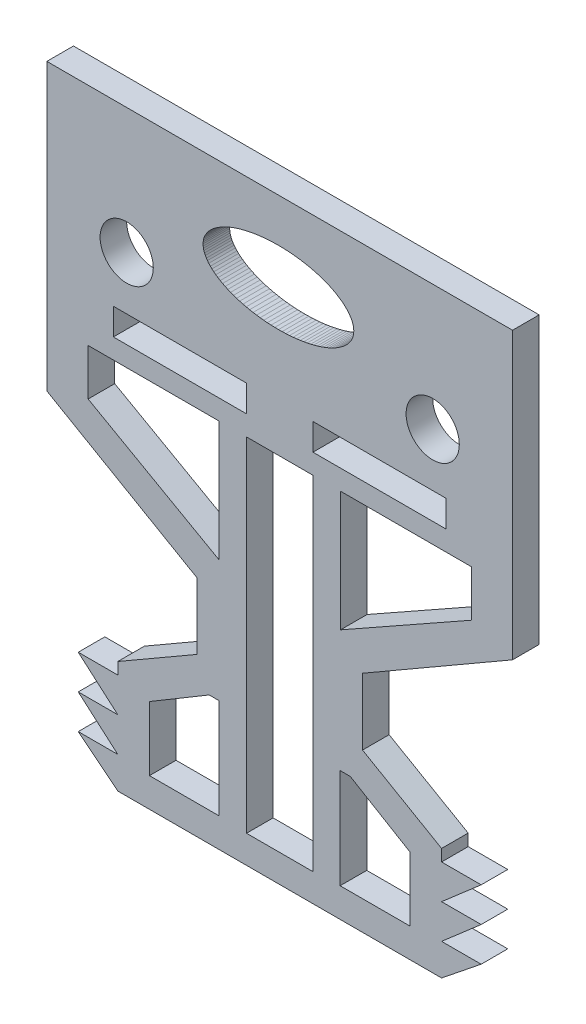
SolidWorks part; units mm, degrees
ref_plane "前视基准面" through (0, 0, 0) normal (0, 0, 1) x (1, 0, 0)
ref_plane "上视基准面" through (0, 0, 0) normal (0, 1, 0) x (1, 0, 0)
ref_plane "右视基准面" through (0, 0, 0) normal (1, 0, 0) x (0, 0, -1)
sketch "Model" plane through (0, 0, 0) normal (0, 0, 1) x (1, 0, 0)
  line L0 (794.8264, 604.0866) -> (759.8264, 604.0866)
  line L1 (789.8264, 590.6477) -> (789.8264, 588.6477)
  line L2 (789.8264, 590.6477) -> (779.8264, 590.6477)
  line L3 (779.8264, 588.6477) -> (779.8264, 590.6477)
  line L4 (774.8264, 590.6477) -> (764.8264, 590.6477)
  line L5 (764.8264, 588.6477) -> (764.8264, 590.6477)
  line L6 (789.8264, 588.6477) -> (779.8264, 588.6477)
  line L7 (774.8264, 588.6477) -> (764.8264, 588.6477)
  line L8 (774.8264, 590.6477) -> (774.8264, 588.6477)
  line L9 (789.4934, 559.2567) -> (765.1593, 559.2567)
  line L10 (783.5518, 576.1218) -> (783.5518, 571.1218)
  line L11 (783.5518, 571.1218) -> (789.4934, 567.6914)
  line L12 (794.8264, 604.0866) -> (794.8264, 582.6312)
  line L13 (759.8264, 604.0866) -> (759.8264, 582.6312)
  line L14 (783.5518, 576.1218) -> (794.8264, 582.6312)
  line L15 (771.101, 576.1218) -> (771.101, 571.1218)
  line L16 (771.101, 571.1218) -> (765.1593, 567.6914)
  line L17 (771.101, 576.1218) -> (759.8264, 582.6312)
  line L18 (792.4681, 566.808) -> (789.4934, 566.808)
  line L19 (792.4681, 564.2247) -> (789.4934, 564.2247)
  line L20 (789.4934, 564.2247) -> (792.4681, 566.808)
  line L21 (792.4681, 561.6414) -> (789.4934, 561.6414)
  line L22 (789.4934, 561.6414) -> (792.4681, 564.2247)
  line L23 (792.4681, 561.6414) -> (789.4934, 559.2567)
  line L24 (789.4934, 566.808) -> (789.4934, 567.6914)
  line L25 (762.1846, 566.808) -> (765.1593, 566.808)
  line L26 (762.1846, 564.2247) -> (765.1593, 564.2247)
  line L27 (765.1593, 564.2247) -> (762.1846, 566.808)
  line L28 (762.1846, 561.6414) -> (765.1593, 561.6414)
  line L29 (765.1593, 561.6414) -> (762.1846, 564.2247)
  line L30 (762.1846, 561.6414) -> (765.1593, 559.2567)
  line L31 (765.1593, 566.808) -> (765.1593, 567.6914)
  line L32 (791.725, 587.1462) -> (781.8947, 587.1462)
  line L33 (781.8947, 587.1462) -> (781.8947, 578.1181)
  line L34 (781.8947, 578.1181) -> (791.725, 583.6595)
  line L35 (791.725, 583.6595) -> (791.725, 587.1462)
  line L36 (779.8203, 587.1462) -> (779.8203, 561.3469)
  line L37 (787.1169, 566.2716) -> (782.6295, 568.9454)
  line L38 (782.6295, 568.9454) -> (781.8695, 568.9454)
  line L39 (781.8695, 568.9454) -> (781.8695, 561.4489)
  line L40 (781.8695, 561.4489) -> (787.1169, 561.4489)
  line L41 (787.1169, 561.4489) -> (787.1169, 566.2716)
  line L42 (762.9277, 587.1462) -> (772.758, 587.1462)
  line L43 (772.758, 587.1462) -> (772.758, 578.1181)
  line L44 (772.758, 578.1181) -> (762.9277, 583.6595)
  line L45 (762.9277, 583.6595) -> (762.9277, 587.1462)
  line L46 (774.8324, 587.1462) -> (774.8324, 561.3469)
  line L47 (774.8324, 587.1462) -> (779.8203, 587.1462)
  line L48 (779.8203, 561.3469) -> (774.8324, 561.3469)
  line L49 (767.5358, 566.2716) -> (772.0232, 568.9454)
  line L50 (772.7832, 568.9454) -> (772.7832, 561.4489)
  line L51 (772.7832, 561.4489) -> (767.5358, 561.4489)
  line L52 (767.5358, 561.4489) -> (767.5358, 566.2716)
  line L53 (772.7832, 568.9454) -> (772.0232, 568.9454)
  line L54 (782.8963, 598.0742) -> (782.8863, 598.2082)
  line L55 (782.8863, 598.2082) -> (782.8663, 598.3432)
  line L56 (782.8663, 598.3432) -> (782.8363, 598.4762)
  line L57 (782.8363, 598.4762) -> (782.7863, 598.6082)
  line L58 (782.7863, 598.6082) -> (782.7263, 598.7402)
  line L59 (782.7263, 598.7402) -> (782.6463, 598.8692)
  line L60 (782.6463, 598.8692) -> (782.5663, 598.9972)
  line L61 (782.5663, 598.9972) -> (782.4663, 599.1222)
  line L62 (782.4663, 599.1222) -> (782.3463, 599.2452)
  line L63 (782.3463, 599.2452) -> (782.2263, 599.3652)
  line L64 (782.2263, 599.3652) -> (782.0863, 599.4832)
  line L65 (782.0863, 599.4832) -> (781.9363, 599.5962)
  line L66 (781.9363, 599.5962) -> (781.7763, 599.7062)
  line L67 (781.7763, 599.7062) -> (781.6063, 599.8122)
  line L68 (781.6063, 599.8122) -> (781.4263, 599.9142)
  line L69 (781.4263, 599.9142) -> (781.2363, 600.0112)
  line L70 (781.2363, 600.0112) -> (781.0363, 600.1042)
  line L71 (781.0363, 600.1042) -> (780.8263, 600.1922)
  line L72 (780.8263, 600.1922) -> (780.6063, 600.2752)
  line L73 (780.6063, 600.2752) -> (780.3763, 600.3522)
  line L74 (780.3763, 600.3522) -> (780.1463, 600.4242)
  line L75 (780.1463, 600.4242) -> (779.8963, 600.4902)
  line L76 (779.8963, 600.4902) -> (779.6563, 600.5512)
  line L77 (779.6563, 600.5512) -> (779.3963, 600.6052)
  line L78 (779.3963, 600.6052) -> (779.1363, 600.6542)
  line L79 (779.1363, 600.6542) -> (778.8763, 600.6962)
  line L80 (778.8763, 600.6962) -> (778.6063, 600.7322)
  line L81 (778.6063, 600.7322) -> (778.3363, 600.7612)
  line L82 (778.3363, 600.7612) -> (778.0663, 600.7842)
  line L83 (778.0663, 600.7842) -> (777.7863, 600.8012)
  line L84 (777.7863, 600.8012) -> (777.5063, 600.8102)
  line L85 (777.5063, 600.8102) -> (777.2363, 600.8142)
  line L86 (777.2363, 600.8142) -> (776.9563, 600.8102)
  line L87 (776.9563, 600.8102) -> (776.6763, 600.8012)
  line L88 (776.6763, 600.8012) -> (776.3963, 600.7842)
  line L89 (776.3963, 600.7842) -> (776.1263, 600.7612)
  line L90 (776.1263, 600.7612) -> (775.8563, 600.7322)
  line L91 (775.8563, 600.7322) -> (775.5863, 600.6962)
  line L92 (775.5863, 600.6962) -> (775.3263, 600.6542)
  line L93 (775.3263, 600.6542) -> (775.0663, 600.6052)
  line L94 (775.0663, 600.6052) -> (774.8063, 600.5512)
  line L95 (774.8063, 600.5512) -> (774.5663, 600.4902)
  line L96 (774.5663, 600.4902) -> (774.3163, 600.4242)
  line L97 (774.3163, 600.4242) -> (774.0863, 600.3522)
  line L98 (774.0863, 600.3522) -> (773.8563, 600.2752)
  line L99 (773.8563, 600.2752) -> (773.6363, 600.1922)
  line L100 (773.6363, 600.1922) -> (773.4263, 600.1042)
  line L101 (773.4263, 600.1042) -> (773.2263, 600.0112)
  line L102 (773.2263, 600.0112) -> (773.0363, 599.9142)
  line L103 (773.0363, 599.9142) -> (772.8563, 599.8122)
  line L104 (772.8563, 599.8122) -> (772.6863, 599.7062)
  line L105 (772.6863, 599.7062) -> (772.5263, 599.5962)
  line L106 (772.5263, 599.5962) -> (772.3763, 599.4832)
  line L107 (772.3763, 599.4832) -> (772.2363, 599.3652)
  line L108 (772.2363, 599.3652) -> (772.1163, 599.2452)
  line L109 (772.1163, 599.2452) -> (771.9963, 599.1222)
  line L110 (771.9963, 599.1222) -> (771.8963, 598.9972)
  line L111 (771.8963, 598.9972) -> (771.8163, 598.8692)
  line L112 (771.8163, 598.8692) -> (771.7363, 598.7402)
  line L113 (771.7363, 598.7402) -> (771.6763, 598.6082)
  line L114 (771.6763, 598.6082) -> (771.6263, 598.4762)
  line L115 (771.6263, 598.4762) -> (771.5963, 598.3432)
  line L116 (771.5963, 598.3432) -> (771.5763, 598.2082)
  line L117 (771.5763, 598.2082) -> (771.5663, 598.0742)
  line L118 (771.5663, 598.0742) -> (771.5763, 597.9402)
  line L119 (771.5763, 597.9402) -> (771.5963, 597.8052)
  line L120 (771.5963, 597.8052) -> (771.6263, 597.6722)
  line L121 (771.6263, 597.6722) -> (771.6763, 597.5402)
  line L122 (771.6763, 597.5402) -> (771.7363, 597.4082)
  line L123 (771.7363, 597.4082) -> (771.8163, 597.2792)
  line L124 (771.8163, 597.2792) -> (771.8963, 597.1512)
  line L125 (771.8963, 597.1512) -> (771.9963, 597.0262)
  line L126 (771.9963, 597.0262) -> (772.1163, 596.9032)
  line L127 (772.1163, 596.9032) -> (772.2363, 596.7832)
  line L128 (772.2363, 596.7832) -> (772.3763, 596.6662)
  line L129 (772.3763, 596.6662) -> (772.5263, 596.5522)
  line L130 (772.5263, 596.5522) -> (772.6863, 596.4422)
  line L131 (772.6863, 596.4422) -> (772.8563, 596.3362)
  line L132 (772.8563, 596.3362) -> (773.0363, 596.2342)
  line L133 (773.0363, 596.2342) -> (773.2263, 596.1372)
  line L134 (773.2263, 596.1372) -> (773.4263, 596.0442)
  line L135 (773.4263, 596.0442) -> (773.6363, 595.9562)
  line L136 (773.6363, 595.9562) -> (773.8563, 595.8732)
  line L137 (773.8563, 595.8732) -> (774.0863, 595.7962)
  line L138 (774.0863, 595.7962) -> (774.3163, 595.7242)
  line L139 (774.3163, 595.7242) -> (774.5663, 595.6582)
  line L140 (774.5663, 595.6582) -> (774.8063, 595.5972)
  line L141 (774.8063, 595.5972) -> (775.0663, 595.5432)
  line L142 (775.0663, 595.5432) -> (775.3263, 595.4942)
  line L143 (775.3263, 595.4942) -> (775.5863, 595.4522)
  line L144 (775.5863, 595.4522) -> (775.8563, 595.4162)
  line L145 (775.8563, 595.4162) -> (776.1263, 595.3872)
  line L146 (776.1263, 595.3872) -> (776.3963, 595.3642)
  line L147 (776.3963, 595.3642) -> (776.6763, 595.3472)
  line L148 (776.6763, 595.3472) -> (776.9563, 595.3382)
  line L149 (776.9563, 595.3382) -> (777.2363, 595.3342)
  line L150 (777.2363, 595.3342) -> (777.5063, 595.3382)
  line L151 (777.5063, 595.3382) -> (777.7863, 595.3472)
  line L152 (777.7863, 595.3472) -> (778.0663, 595.3642)
  line L153 (778.0663, 595.3642) -> (778.3363, 595.3872)
  line L154 (778.3363, 595.3872) -> (778.6063, 595.4162)
  line L155 (778.6063, 595.4162) -> (778.8763, 595.4522)
  line L156 (778.8763, 595.4522) -> (779.1363, 595.4942)
  line L157 (779.1363, 595.4942) -> (779.3963, 595.5432)
  line L158 (779.3963, 595.5432) -> (779.6563, 595.5972)
  line L159 (779.6563, 595.5972) -> (779.8963, 595.6582)
  line L160 (779.8963, 595.6582) -> (780.1463, 595.7242)
  line L161 (780.1463, 595.7242) -> (780.3763, 595.7962)
  line L162 (780.3763, 595.7962) -> (780.6063, 595.8732)
  line L163 (780.6063, 595.8732) -> (780.8263, 595.9562)
  line L164 (780.8263, 595.9562) -> (781.0363, 596.0442)
  line L165 (781.0363, 596.0442) -> (781.2363, 596.1372)
  line L166 (781.2363, 596.1372) -> (781.4263, 596.2342)
  line L167 (781.4263, 596.2342) -> (781.6063, 596.3362)
  line L168 (781.6063, 596.3362) -> (781.7763, 596.4422)
  line L169 (781.7763, 596.4422) -> (781.9363, 596.5522)
  line L170 (781.9363, 596.5522) -> (782.0863, 596.6662)
  line L171 (782.0863, 596.6662) -> (782.2263, 596.7832)
  line L172 (782.2263, 596.7832) -> (782.3463, 596.9032)
  line L173 (782.3463, 596.9032) -> (782.4663, 597.0262)
  line L174 (782.4663, 597.0262) -> (782.5663, 597.1512)
  line L175 (782.5663, 597.1512) -> (782.6463, 597.2792)
  line L176 (782.6463, 597.2792) -> (782.7263, 597.4082)
  line L177 (782.7263, 597.4082) -> (782.7863, 597.5402)
  line L178 (782.7863, 597.5402) -> (782.8363, 597.6722)
  line L179 (782.8363, 597.6722) -> (782.8663, 597.8052)
  line L180 (782.8663, 597.8052) -> (782.8863, 597.9402)
  line L181 (782.8863, 597.9402) -> (782.8963, 598.0742)
  circle A0 centre (765.8264, 594.6473) radius 2
  circle A1 centre (788.8264, 594.6473) radius 2
extrude "凸台-拉伸1" add sketch "Model" along normal blind 2
